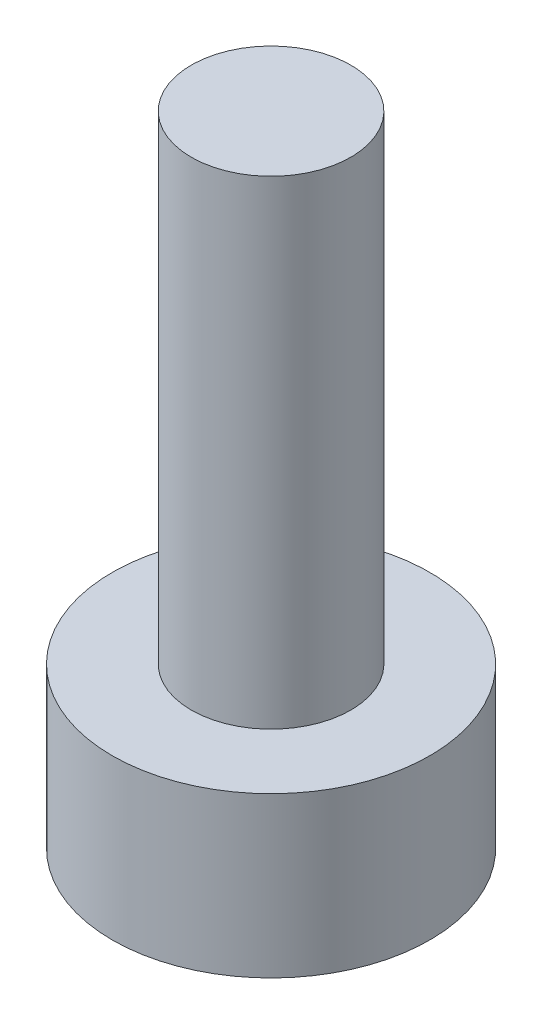
SolidWorks part; units mm, degrees
other "Retainer Screw ISO4762 M2x6"
ref_plane "Front Plane" through (0, 0, 0) normal (0, 0, 1) x (1, 0, 0)
ref_plane "Top Plane" through (0, 0, 0) normal (0, 1, 0) x (1, 0, 0)
ref_plane "Right Plane" through (0, 0, 0) normal (1, 0, 0) x (0, 0, -1)
sketch3d "M2x6 full-thread envelope sketch datum points"
  point P0 (-26.2917, -73, -8.5)
  point P1 (-16.2917, -73, -8.5)
  point P2 (-26.2917, -73, -18.5)
ref_plane "M2x6 full-thread envelope sketch plane" through (0, -73, 0) normal (0, 1, 0) x (1, 0, 0)
sketch "M2x6 full-thread envelope sketch" plane through (0, -73, 0) normal (0, 1, 0) x (1, 0, 0)
  circle A0 centre (-26.2917, 8.5) radius 1
extrude "M2x6 full-thread envelope" add sketch "M2x6 full-thread envelope sketch" along normal blind 6 separate body
sketch3d "Purchased DIN912 maximum head sketch datum points"
  point P0 (-26.2917, -75, -8.5)
  point P1 (-16.2917, -75, -8.5)
  point P2 (-26.2917, -75, -18.5)
ref_plane "Purchased DIN912 maximum head sketch plane" through (0, -75, 0) normal (0, 1, 0) x (1, 0, 0)
sketch "Purchased DIN912 maximum head sketch" plane through (0, -75, 0) normal (0, 1, 0) x (1, 0, 0)
  circle A0 centre (-26.2917, 8.5) radius 1.99
extrude "Purchased DIN912 maximum head" add sketch "Purchased DIN912 maximum head sketch" along normal blind 2
